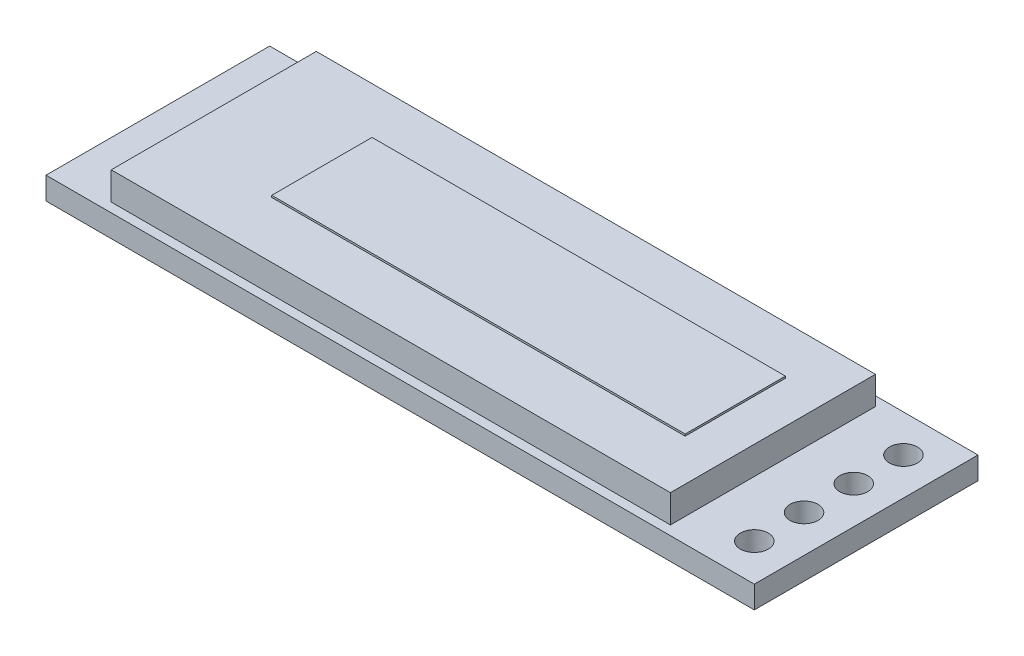
SolidWorks part; units mm, degrees
ref_plane "Спереди" through (0, 0, 0) normal (0, 0, 1) x (1, 0, 0)
ref_plane "Сверху" through (0, 0, 0) normal (0, 1, 0) x (1, 0, 0)
ref_plane "Справа" through (0, 0, 0) normal (1, 0, 0) x (0, 0, -1)
sketch "Эскиз1" plane through (0, 0, 0) normal (0, 1, 0) x (1, 0, 0)
  line L1 (0, 6) -> (-38, 6)
  line L2 (0, 6) -> (0, -6)
  line L3 (0, -6) -> (-38, -6)
  line L4 (-38, 6) -> (-38, -6)
  dimension "D1" = 12
  dimension "D2" = 38
extrude "Бобышка-Вытянуть1" add sketch "Эскиз1" along normal blind 1.2
sketch "Эскиз2" plane through (0, 0, 0) normal (0, 1, 0) x (1, 0, 0)
  line L1 (-5, 5.5) -> (-35, 5.5)
  line L2 (-5, 5.5) -> (-5, -5.5)
  line L3 (-5, -5.5) -> (-35, -5.5)
  line L4 (-35, 5.5) -> (-35, -5.5)
  line L5 (-38, 6) -> (-38, -6) construction
  line L6 (0, 0) -> (-5, 0) construction
  dimension "D1" = 11
  dimension "D2" = 35
  dimension "D3" = 33
extrude "Бобышка-Вытянуть2" add sketch "Эскиз2" along normal blind 2.7
sketch "Эскиз3" plane through (0, 0, 0) normal (0, 1, 0) x (1, 0, 0)
  line L0 (-2, 1.3333) -> (-2, -1.3333) construction
  line L1 (-2, 0) -> (0, 0) construction
  line L2 (0, 6) -> (-38, 6) construction
  line L3 (0, -6) -> (0, 6) construction
  circle A0 centre (-2, 4) radius 0.75
  circle A1 centre (-2, 1.3333) radius 0.75
  circle A2 centre (-2, -1.3333) radius 0.75
  circle A3 centre (-2, -4) radius 0.75
  dimension "D2" = 1.5
  dimension "D3" = 2
  dimension "D4" = 2
  dimension "D1" = 4
extrude "Вырез-Вытянуть2" cut sketch "Эскиз3" along normal through all
sketch "Эскиз4" plane through (0, 0, 0) normal (0, 1, 0) x (1, 0, 0)
  line L0 (-38, 6) -> (-38, -6) construction
  line L1 (-24, -5) -> (-22, -5)
  line L2 (-24, -5) -> (-24, 5)
  line L3 (-24, 5) -> (-22, 5)
  line L4 (-22, -5) -> (-22, 5)
  line L5 (0, 0) -> (-24, 0) construction
  line L6 (-17, -5) -> (-15, -5)
  line L7 (-17, -5) -> (-17, 5)
  line L8 (-17, 5) -> (-15, 5)
  line L9 (-15, -5) -> (-15, 5)
  line L10 (0, -6) -> (0, 6) construction
  line L11 (-38, -6) -> (0, -6) construction
  line L13 (-11.3273, 1.2331) -> (-9.3273, 1.2331)
  line L14 (-11.3273, 1.2331) -> (-11.3273, 2.6033)
  line L15 (-11.3273, 2.6033) -> (-9.3273, 2.6033)
  line L16 (-9.3273, 1.2331) -> (-9.3273, 2.6033)
  point P14 (-15, 0)
  dimension "D1" = 16
  dimension "D2" = 2
  dimension "D3" = 23
  dimension "D4" = 1
extrude "Бобышка-Вытянуть3" add sketch "Эскиз4" against normal blind 2 from surface at 1.2 starting at face at (-2, 1.2, -4.75)
sketch "Эскиз5" plane through (0, 2.7, 0) normal (0, 1, 0) x (1, 0, 0)
  line L0 (0, 0) -> (-7.13, 0) construction
  line L1 (0, -6) -> (0, 6) construction
  line L2 (-38, 0) -> (-29.51, 0) construction
  line L3 (-38, 6) -> (-38, -6) construction
  line L4 (-19, 6) -> (-19, 3) construction
  line L5 (0, 6) -> (-38, 6) construction
  line L6 (-19, -6) -> (-19, -2.58) construction
  line L7 (-38, -6) -> (0, -6) construction
  line L8 (-29.41, 2.9) -> (-29.41, -2.48)
  line L9 (-29.51, 3) -> (-7.13, 3) construction
  line L10 (-29.51, 3) -> (-29.51, -2.58) construction
  line L11 (-29.51, -2.58) -> (-7.13, -2.58) construction
  line L12 (-7.13, 3) -> (-7.13, -2.58) construction
  line L13 (-29.41, -2.48) -> (-7.23, -2.48)
  line L14 (-7.23, 2.9) -> (-7.23, -2.48)
  line L15 (-29.41, 2.9) -> (-7.23, 2.9)
  line L16 (-7.23, 0.21) -> (-29.41, 0.21) construction
  dimension "D1" = 7.13
  dimension "D2" = 8.49
  dimension "D3" = 3
  dimension "D4" = 3.42
  dimension "D5" = 0.1
ref_plane "Плоскость1" through (-19, 0, 0) normal (1, 0, 0) x (0, 0, -1)
extrude "Бобышка-Вытянуть4" add sketch "Эскиз5" along normal blind 0.1
ref_plane "Плоскость2" through (0, 0, -0.21) normal (0, 0, -1) x (-1, 0, 0)
